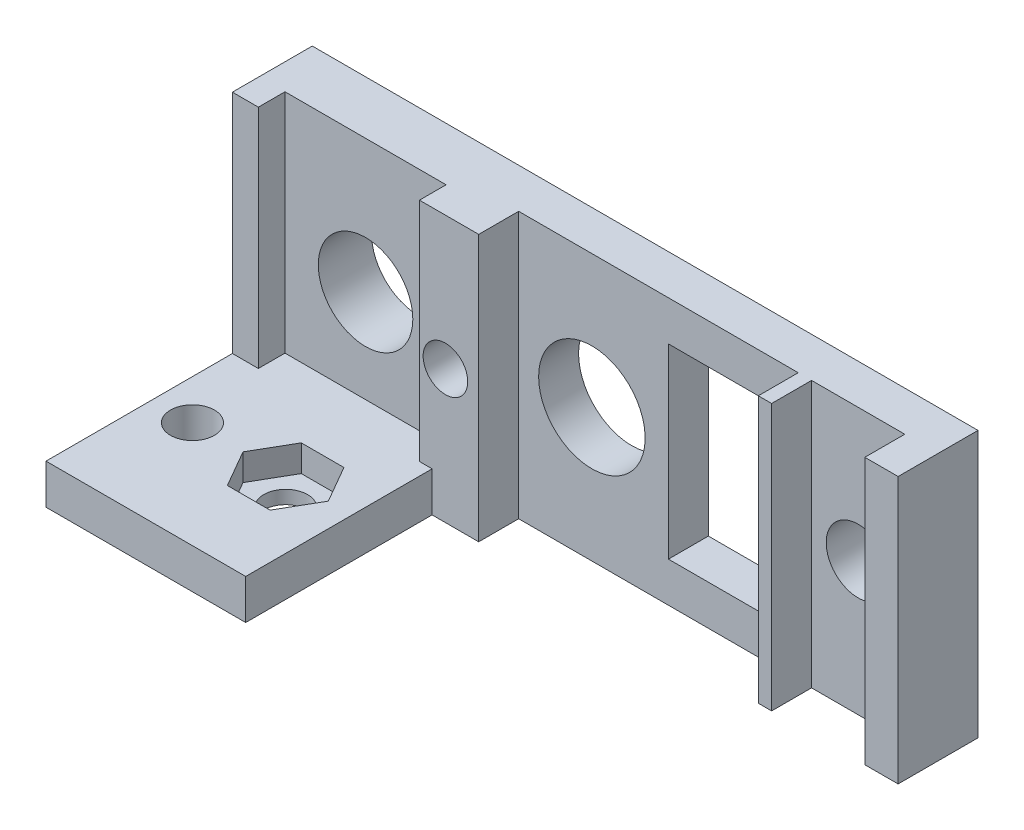
SolidWorks part; units mm, degrees
ref_plane "Front Plane" through (0, 0, 0) normal (0, 0, 1) x (1, 0, 0)
ref_plane "Top Plane" through (0, 0, 0) normal (0, 1, 0) x (1, 0, 0)
ref_plane "Right Plane" through (0, 0, 0) normal (1, 0, 0) x (0, 0, -1)
sketch "Sketch1" plane through (0, 0, 0) normal (0, 0, 1) x (1, 0, 0)
  line L0 (-25, 0) -> (25, 0) construction
  line L1 (25, -10) -> (-25, -10)
  line L2 (25, -10) -> (25, 10)
  line L3 (25, 10) -> (-25, 10)
  line L4 (-25, -10) -> (-25, 10)
  line L5 (25, -10) -> (-25, 10) construction
  line L6 (25, 10) -> (-25, -10) construction
  line L7 (4.75, -7) -> (13.25, -7)
  line L8 (4.75, -7) -> (4.75, 7)
  line L9 (4.75, 7) -> (13.25, 7)
  line L10 (13.25, -7) -> (13.25, 7)
  line L11 (4.75, -7) -> (13.25, 7) construction
  line L12 (4.75, 7) -> (13.25, -7) construction
  circle A0 centre (-17, 0) radius 3.55
  circle A1 centre (-9, 0) radius 1.675
  circle A2 centre (-1, 0) radius 4
  circle A3 centre (19, 0) radius 2.4
  point P0 (0, 0)
  point P12 (9, 0)
  dimension "D3" = 7.1
  dimension "D4" = 8
  dimension "D5" = 3.35
  dimension "D6" = 8
  dimension "D7" = 8
  dimension "D8" = 8
  dimension "D12" = 10
  dimension "D11" = 4.8
  dimension "D1" = 50
  dimension "D2" = 20
  dimension "D9" = 8.5
  dimension "D10" = 14
  dimension "10" = 10
extrude "Boss-Extrude1" add sketch "Sketch1" along normal blind 6
sketch "Sketch3" plane through (0, 0, 6) normal (0, 0, 1) x (1, 0, 0)
  line L0 (25, 10) -> (-25, 10) construction
  line L1 (14.5, -10) -> (3.5, -10)
  line L2 (14.5, -10) -> (14.5, 10)
  line L3 (14.5, 10) -> (3.5, 10)
  line L4 (3.5, -10) -> (3.5, 10)
  line L5 (14.5, -10) -> (3.5, 10) construction
  line L6 (14.5, 10) -> (3.5, -10) construction
  line L7 (-25, -10) -> (25, -10) construction
  line L8 (13.25, -7) -> (13.25, 7) construction
  point P0 (9, 0)
  dimension "D1" = 11
  dimension "D2" = 4.25
extrude "Cut-Extrude2" cut sketch "Sketch3" against normal blind 3
sketch "Sketch4" plane through (0, 0, 6) normal (0, 0, 1) x (1, 0, 0)
  line L0 (3.5, 10) -> (-25, 10) construction
  line L1 (-10.95, -10) -> (-23.05, -10)
  line L2 (-10.95, -10) -> (-10.95, 10)
  line L3 (-10.95, 10) -> (-23.05, 10)
  line L4 (-23.05, -10) -> (-23.05, 10)
  line L5 (-10.95, -10) -> (-23.05, 10) construction
  line L6 (-10.95, 10) -> (-23.05, -10) construction
  point P0 (-17, 0)
  dimension "D1" = 12.1
extrude "Cut-Extrude4" cut sketch "Sketch4" against normal blind 2
sketch "Sketch6" plane through (0, -10, 0) normal (0, -1, 0) x (1, 0, 0)
  line L1 (-25, 0) -> (-10, 0)
  line L2 (-25, 0) -> (-25, 20)
  line L3 (-25, 20) -> (-10, 20)
  line L4 (-10, 0) -> (-10, 20)
  dimension "D1" = 20
  dimension "D2" = 15
extrude "Boss-Extrude3" add sketch "Sketch6" along normal blind 3 from offset 3 offset against normal yes
sketch "Sketch7" plane through (0, -7, 0) normal (0, 1, 0) x (1, 0, 0)
  line L0 (-10, -20) -> (-25, -20) construction
  line L7 (-25, -20) -> (-25, -6) construction
  circle A0 centre (-22, -12) radius 1.65
  circle A1 centre (-15, -12) radius 1.65
  point P15 (0, 0)
  dimension "D1" = 3.3
  dimension "D3" = 3.3
  dimension "D4" = 8
  dimension "D5" = 3
extrude "Cut-Extrude5" cut sketch "Sketch7" against normal blind 3
sketch "Sketch8" plane through (0, -7, 0) normal (0, 1, 0) x (1, 0, 0)
  line L0 (-10, -20) -> (-25, -20) construction
  line L1 (-13.3979, -9.225) -> (-16.6021, -9.225)
  line L2 (-16.6021, -9.225) -> (-18.2043, -12)
  line L3 (-18.2043, -12) -> (-16.6021, -14.775)
  line L4 (-16.6021, -14.775) -> (-13.3979, -14.775)
  line L5 (-13.3979, -14.775) -> (-11.7957, -12)
  line L6 (-11.7957, -12) -> (-13.3979, -9.225)
  circle A0 centre (-15, -12) radius 2.775 construction
  dimension "D1" = 5.55
extrude "Cut-Extrude6" cut sketch "Sketch8" against normal blind 2
sketch "Sketch10" plane through (0, 0, 6) normal (0, 0, 1) x (1, 0, 0)
  line L0 (25, 10) -> (14.5, 10) construction
  line L1 (15.5, 10) -> (22.5, 10)
  line L2 (15.5, 10) -> (15.5, -10)
  line L3 (15.5, -10) -> (22.5, -10)
  line L4 (22.5, 10) -> (22.5, -10)
  line L5 (14.5, -10) -> (25, -10) construction
  line L6 (-10, -10) -> (3.5, -10) construction
  line L7 (3.5, 10) -> (-6.5, 10)
  line L8 (3.5, 10) -> (3.5, -10)
  line L9 (3.5, -10) -> (-6.5, -10)
  line L10 (-6.5, 10) -> (-6.5, -10)
  circle A0 centre (19, 0) radius 2.4 construction
  dimension "D2" = 3.5
  dimension "D1" = 10
  dimension "7" = 7
extrude "Cut-Extrude7" cut sketch "Sketch10" against normal blind 3
